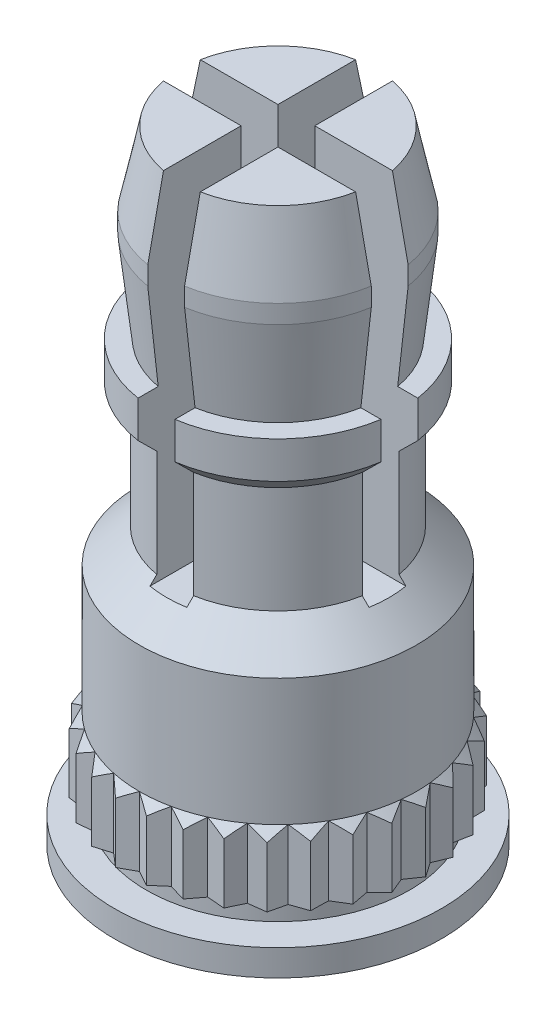
SolidWorks part; units mm, degrees
revolve "Body" add sketch "BodySke" angle 360 about L9
sketch "BodySke" plane through (0, 0, 0) normal (0, 0, 1) x (1, 0, 0)
  line L0 (2.5555, 0) -> (2.5555, 0.3825)
  line L1 (2.69, 4.1891) -> (2.0272, 4.8518)
  line L2 (2.87, 1.5475) -> (2.69, 1.7275)
  line L3 (2.0272, 4.8518) -> (2.0272, 6.9267)
  line L4 (0, -0.51) -> (3.175, -0.51)
  line L5 (3.175, -0.51) -> (3.175, 0)
  line L6 (3.175, 0) -> (2.5555, 0)
  line L7 (2.385, 7.2845) -> (2.385, 8)
  line L8 (2.69, 1.7275) -> (2.69, 4.1891)
  line L9 (0, -0.51) -> (0, 17.145) construction
  line L10 (2.385, 8) -> (2, 8)
  line L11 (2, 8) -> (2.2, 9.79)
  line L12 (2.2, 9.79) -> (2.2, 10.148)
  line L13 (2.2, 10.148) -> (1.9, 11.58)
  line L14 (1.9, 11.58) -> (0, 11.58)
  line L15 (2.5555, 0.3825) -> (2.87, 0.3825)
  line L16 (2.87, 0.3825) -> (2.87, 1.5475)
  line L17 (0, 11.58) -> (0, -0.51)
  line L19 (2.385, 7.2845) -> (2.0272, 6.9267)
  dimension "H_dia" = 6.35
  dimension "C_dia" = 5.38
  dimension "Clinch_dia" = 5.74
  dimension "Groove_dia" = 5.111
  dimension "T_ht" = 0.51
  dimension "Groove_wid" = 0.3825
  dimension "Clinch_lim" = 1.345
  dimension "Length" = 8
  dimension "D_ht" = 3.58
  dimension "D4" = 45
  dimension "Neck_dia" = 4.0545
  dimension "B_dia" = 4.77
  dimension "B_ht" = 0.7155
  dimension "Panel_dia" = 4
  dimension "Slip_dia" = 4.4
  dimension "Tip_dia" = 3.8
  dimension "Grip_ht" = 1.79
  dimension "Slip_ht" = 0.358
  dimension "Neck_len" = 3.1482
ref_plane "Plane1" through (0, 0, 0) normal (0, 0, 1) x (1, 0, 0)
ref_plane "Plane2" through (0, 0, 0) normal (0, 1, 0) x (1, 0, 0)
ref_plane "Plane3" through (0, 0, 0) normal (1, 0, 0) x (0, 0, -1)
sketch "SlitCutSke" plane through (0, 11.58, 0) normal (0, 1, 0) x (-1, 0, 0)
  line L0 (-2.6661, 0.3578) -> (2.6661, 0.3578)
  line L1 (2.6661, -0.3578) -> (-2.6661, -0.3578)
  line L2 (-2.6661, 0.3578) -> (-2.6661, -0.3578)
  line L3 (2.6661, 0.3578) -> (2.6661, -0.3578)
  line L4 (-4.064, 0) -> (4.064, 0) construction
  circle A1 centre (0, 0) radius 2.69 construction
extrude "SlitCut" cut sketch "SlitCutSke" against normal blind 6.8582
pattern_circular "SlitCutPat" count 2 every 90 about axis through (0, -0.51, 0) along (0, 1, 0) of "SlitCut"
ref_plane "Plane4" through (0, -0.5486, 0) normal (0, 1, 0) x (-1, 0, 0)
sketch "CliRinCutSke" plane through (0, 0.3825, 0) normal (0, -1, 0) x (1, 0, 0)
  line L0 (0.3, 2.8543) -> (0, 2.69)
  line L1 (0, 2.69) -> (-0.3, 2.8543)
  line L2 (0, 0) -> (0, 5.842) construction
  arc A1 (0.3, 2.8543) -> (-0.3, 2.8543) centre (0, 0) ccw
  circle A2 centre (0, 0) radius 2.69 construction
  dimension "Clinch_dia" = 5.74
  dimension "Angle" = 12
extrude "ClinchCut" cut sketch "CliRinCutSke" against normal blind 1.345
pattern_circular "ClinchCutPat" count 30 every 12 about axis through (0, -0.51, 0) along (0, 1, 0) of "ClinchCut"
equation "' \"Panel_dia@BodySke\" = 4"
equation "' \"Length@BodySke\" = 8"
equation "' \"B_dia@BodySke\" = 4.77"
equation "' \"C_dia@BodySke\" = 5.38"
equation "' \"D_ht@BodySke\" = 3.58"
equation "' \"H_dia@BodySke\" = 6.35"
equation "' \"T_ht@BodySke\" = 0.51"
equation "' \"Clinch_dia@BodySke\" = 5.74"
equation "\"Tip_dia@BodySke\" = \"Panel_dia@BodySke\" * 0.95"
equation "\"Slip_dia@BodySke\" = \"Panel_dia@BodySke\" * 1.1"
equation "\"Slip_ht@BodySke\" = \"D_ht@BodySke\" * 0.1"
equation "\"Grip_ht@BodySke\" = \"D_ht@BodySke\" * 0.5"
equation "\"B_ht@BodySke\" = \"B_dia@BodySke\" * 0.15"
equation "\"Neck_dia@BodySke\" = \"B_dia@BodySke\" * 0.85"
equation "\"Neck_len@BodySke\" = \"B_dia@BodySke\" * 0.66"
equation "\"Groove_dia@BodySke\" = \"C_dia@BodySke\" * 0.95"
equation "\"Groove_wid@BodySke\" = \"T_ht@BodySke\" * 0.75"
equation "\"Width@SlitCutSke\" = \"B_ht@BodySke\""
equation "\"Depth@SlitCut\" = \"D_ht@BodySke\" + \"Neck_len@BodySke\" + 0.13"
equation "\"Clinch_lim@BodySke\" = \"C_dia@BodySke\" * 0.25"
equation "\"Count@ClinchCutPat\" = 30"
equation "\"Angle@ClinchCutPat\" = 360 / \"Count@ClinchCutPat\""
equation "\"Angle@CliRinCutSke\" = 360 / \"Count@ClinchCutPat\""
equation "\"Clinch_dia@CliRinCutSke\" = \"Clinch_dia@BodySke\""
equation "\"Clinch_minor@CliRinCutSke\" = \"C_dia@BodySke\""
equation "\"Depth@ClinchCut\" = \"Clinch_lim@BodySke\""
